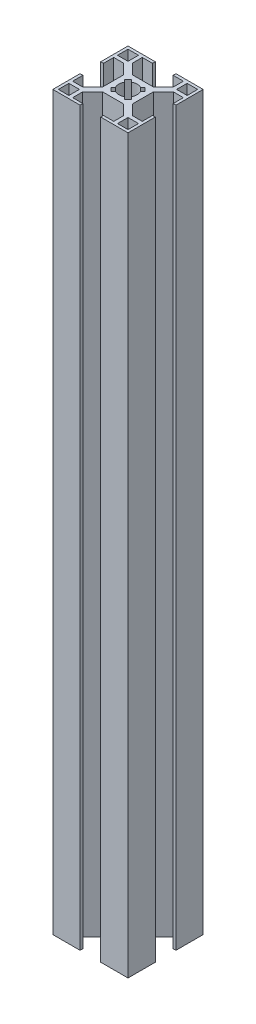
SolidWorks part; units mm, degrees
material "3.0255 (EN-AW 1350A)"
ref_plane "Alzado" through (0, 0, 0) normal (0, 0, 1) x (1, 0, 0)
ref_plane "Planta" through (0, 0, 0) normal (0, 1, 0) x (1, 0, 0)
ref_plane "Vista lateral" through (0, 0, 0) normal (1, 0, 0) x (0, 0, -1)
sketch "Croquis2" plane through (0, 0, 0) normal (0, 1, 0) x (1, 0, 0)
  line L0 (-12.6732, 23.1711) -> (-8.4732, 23.1711)
  line L1 (-37.3732, 24.2711) -> (-26.4982, 24.2711)
  line L2 (-37.3732, 24.2711) -> (-37.3732, 13.3961)
  line L3 (-37.3732, -5.7289) -> (-26.4982, -5.7289)
  line L4 (-7.3732, 24.2711) -> (-7.3732, 13.3961)
  line L5 (-30.5732, -4.6289) -> (-26.4982, -4.6289)
  line L6 (-30.5732, 23.1711) -> (-26.4982, 23.1711)
  line L7 (-36.2732, 5.1461) -> (-37.3732, 5.1461)
  line L8 (-8.4732, 23.1711) -> (-8.4732, 18.9711)
  line L9 (-36.2732, -4.6289) -> (-32.0732, -4.6289)
  line L10 (-36.2732, 23.1711) -> (-36.2732, 18.9711)
  line L11 (-36.2732, 23.1711) -> (-32.0732, 23.1711)
  line L12 (-32.0732, -0.4289) -> (-36.2732, -0.4289)
  line L15 (-8.4732, 18.9711) -> (-12.6732, 18.9711)
  line L16 (-12.6732, 23.1711) -> (-12.6732, 18.9711)
  line L17 (-32.0732, -0.4289) -> (-32.0732, -4.6289)
  line L19 (-36.2732, -0.4289) -> (-36.2732, -4.6289)
  line L21 (-32.0732, 23.1711) -> (-32.0732, 18.9711)
  line L22 (-32.0732, 18.9711) -> (-36.2732, 18.9711)
  line L24 (-8.4732, -0.4289) -> (-12.6732, -0.4289)
  line L25 (-8.4732, -0.4289) -> (-8.4732, -4.6289)
  line L26 (-8.4732, -4.6289) -> (-12.6732, -4.6289)
  line L27 (-12.6732, -0.4289) -> (-12.6732, -4.6289)
  line L28 (-26.5862, 3.3611) -> (-18.1603, 3.3611)
  line L29 (-16.4632, 13.4841) -> (-16.4632, 5.0582)
  line L30 (-26.5862, 15.1811) -> (-18.1603, 15.1811)
  line L31 (-28.2832, 13.4841) -> (-28.2832, 5.0582)
  line L32 (-28.2832, 15.1811) -> (-16.4632, 15.1811) construction
  line L33 (-28.2832, 3.3611) -> (-16.4632, 3.3611) construction
  line L34 (-7.3732, 5.1461) -> (-8.4732, 5.1461)
  line L35 (-7.3732, 13.3961) -> (-8.4732, 13.3961)
  line L36 (-26.4982, 24.2711) -> (-26.4982, 23.1711)
  line L37 (-18.2482, 24.2711) -> (-18.2482, 23.1711)
  line L38 (-36.2732, 13.3961) -> (-37.3732, 13.3961)
  line L39 (-19.1655, 11.0646) -> (-18.2482, 11.9819)
  line L40 (-36.2732, 5.1461) -> (-36.2732, 1.0711)
  line L41 (-36.2732, 23.1711) -> (-36.2732, -4.6289) construction
  line L42 (-37.3732, 5.1461) -> (-37.3732, -5.7289)
  line L43 (-37.3732, 24.2711) -> (-37.3732, -5.7289) construction
  line L44 (-18.2482, -4.6289) -> (-18.2482, -5.7289)
  line L46 (-8.4732, 5.1461) -> (-8.4732, 1.0711)
  line L47 (-8.4732, 23.1711) -> (-8.4732, -4.6289) construction
  line L48 (-7.3732, 5.1461) -> (-7.3732, -5.7289)
  line L49 (-7.3732, 24.2711) -> (-7.3732, -5.7289) construction
  line L51 (-25.084, 5.1461) -> (-24.1667, 6.0634)
  line L52 (-18.2482, -4.6289) -> (-14.1732, -4.6289)
  line L53 (-36.2732, -4.6289) -> (-8.4732, -4.6289) construction
  line L54 (-18.2482, -5.7289) -> (-7.3732, -5.7289)
  line L55 (-37.3732, -5.7289) -> (-7.3732, -5.7289) construction
  line L56 (-16.4632, 15.1811) -> (-16.4632, 3.3611) construction
  line L57 (-26.4982, 11.9819) -> (-25.5809, 11.0646)
  line L58 (-18.2482, 23.1711) -> (-14.1732, 23.1711)
  line L59 (-36.2732, 23.1711) -> (-8.4732, 23.1711) construction
  line L60 (-18.2482, 24.2711) -> (-7.3732, 24.2711)
  line L61 (-37.3732, 24.2711) -> (-7.3732, 24.2711) construction
  line L62 (-32.2703, 1.0711) -> (-36.2732, 1.0711)
  line L63 (-30.5732, 1.0711) -> (-37.7732, 1.0711) construction
  line L64 (-30.5732, 1.0711) -> (-30.5732, -6.1289) construction
  line L65 (-30.5732, -0.6259) -> (-30.5732, -4.6289)
  line L66 (-8.4732, 1.0711) -> (-12.4762, 1.0711)
  line L67 (-14.1732, -0.6259) -> (-14.1732, -4.6289)
  line L68 (-6.9732, 1.0711) -> (-6.9732, -6.1289) construction
  line L69 (-30.5732, -0.6259) -> (-26.5862, 3.3611)
  line L70 (-6.9732, 17.4711) -> (-14.1732, 17.4711) construction
  line L71 (-8.4732, 17.4711) -> (-12.4762, 17.4711)
  line L72 (-14.1732, 23.1711) -> (-14.1732, 19.1682)
  line L73 (-8.4732, 17.4711) -> (-8.4732, 13.3961)
  line L74 (-32.2703, 17.4711) -> (-36.2732, 17.4711)
  line L75 (-30.5732, 24.6711) -> (-30.5732, 17.4711) construction
  line L76 (-16.4632, 13.4841) -> (-12.4762, 17.4711)
  line L77 (-30.5732, 23.1711) -> (-30.5732, 19.1682)
  line L78 (-30.5732, -6.1289) -> (-37.7732, -6.1289) construction
  line L79 (-37.7732, 1.0711) -> (-37.7732, -6.1289) construction
  line L80 (-26.4982, -4.6289) -> (-26.4982, -5.7289)
  line L81 (-30.5732, 19.1682) -> (-26.5862, 15.1811)
  line L83 (-18.1603, 3.3611) -> (-14.1732, -0.6259)
  line L84 (-30.5732, 17.4711) -> (-37.7732, 17.4711) construction
  line L85 (-37.7732, 24.6711) -> (-37.7732, 17.4711) construction
  line L86 (-30.5732, 24.6711) -> (-37.7732, 24.6711) construction
  line L87 (-36.2732, 17.4711) -> (-36.2732, 13.3961)
  line L88 (-32.2703, 1.0711) -> (-28.2832, 5.0582)
  line L90 (-6.9732, -6.1289) -> (-14.1732, -6.1289) construction
  line L91 (-14.1732, 1.0711) -> (-14.1732, -6.1289) construction
  line L92 (-6.9732, 1.0711) -> (-14.1732, 1.0711) construction
  line L94 (-25.084, 13.3961) -> (-24.1667, 12.4788)
  line L95 (-19.1655, 7.4777) -> (-18.2482, 6.5603)
  line L96 (-20.5798, 6.0634) -> (-19.6624, 5.1461)
  line L97 (-14.1732, 24.6711) -> (-14.1732, 17.4711) construction
  line L98 (-6.9732, 24.6711) -> (-14.1732, 24.6711) construction
  line L99 (-6.9732, 24.6711) -> (-6.9732, 17.4711) construction
  line L100 (-16.4632, 5.0582) -> (-12.4762, 1.0711)
  line L101 (-26.4982, 6.5603) -> (-25.5809, 7.4777)
  line L104 (-28.2832, 15.1811) -> (-28.2832, 3.3611) construction
  line L105 (-18.1603, 15.1811) -> (-14.1732, 19.1682)
  line L106 (-32.2703, 17.4711) -> (-28.2832, 13.4841)
  line L111 (-20.5798, 12.4788) -> (-19.6624, 13.3961)
  line L114 (-26.4982, 6.5603) -> (-25.084, 5.1461)
  line L115 (-19.6624, 5.1461) -> (-18.2482, 6.5603)
  line L116 (-19.6624, 13.3961) -> (-18.2482, 11.9819)
  line L117 (-25.084, 13.3961) -> (-26.4982, 11.9819)
  line L119 (-32.0732, 23.1711) -> (-36.2732, 23.1711) construction
  line L120 (-8.4732, 23.1711) -> (-12.6732, 23.1711) construction
  line L121 (-32.0732, -4.6289) -> (-36.2732, -4.6289) construction
  line L122 (-8.4732, 23.1711) -> (-8.4732, 18.9711) construction
  line L123 (-36.2732, 23.1711) -> (-36.2732, 18.9711) construction
  arc A0 (-25.5809, 11.0646) -> (-25.5809, 7.4777) centre (-22.3732, 9.2711) ccw
  arc A1 (-20.5798, 12.4788) -> (-24.1667, 12.4788) centre (-22.3732, 9.2711) ccw
  arc A2 (-19.1655, 7.4777) -> (-19.1655, 11.0646) centre (-22.3732, 9.2711) ccw
  arc A3 (-24.1667, 6.0634) -> (-20.5798, 6.0634) centre (-22.3732, 9.2711) ccw
  dimension "D1" = 30
  dimension "D2" = 30
  dimension "D5" = 1.5
extrude "Saliente-Extruir1" add sketch "Croquis2" along normal blind 292.1
